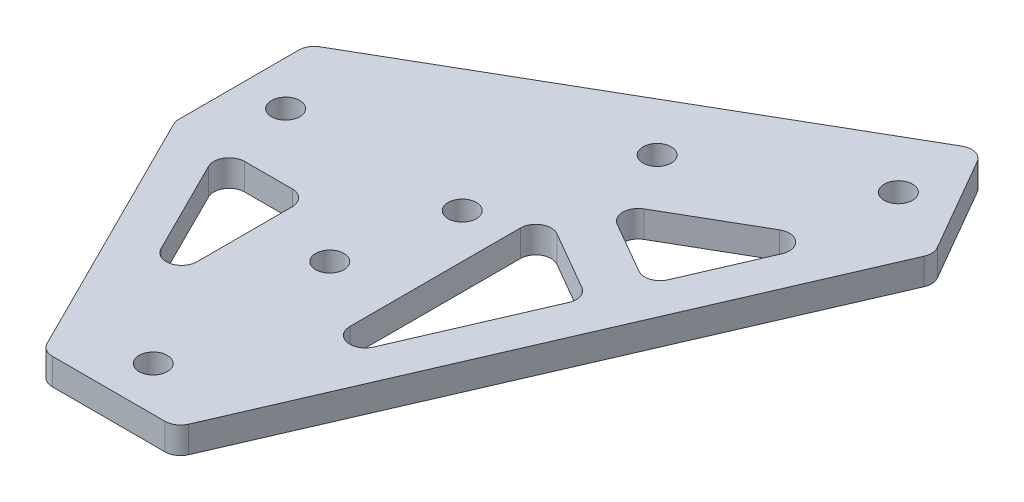
SolidWorks part; units mm, degrees
ref_plane "正面" through (0, 0, 0) normal (0, 0, 1) x (1, 0, 0)
ref_plane "平面" through (0, 0, 0) normal (0, 1, 0) x (1, 0, 0)
ref_plane "右側面" through (0, 0, 0) normal (1, 0, 0) x (0, 0, -1)
sketch "ｽｹｯﾁ2" plane through (0, 0.3953, 0) normal (0, 1, 0) x (1, 0, 0)
  line L0 (275.032, 154.7676) -> (267.532, 167.7579) construction
  line L1 (267.532, 167.7579) -> (163.6089, 107.7579) construction
  line L2 (163.6089, 107.7579) -> (171.1089, 94.7676) construction
  line L3 (171.1089, 94.7676) -> (275.032, 154.7676) construction
  line L4 (171.1089, 79.7676) -> (156.1089, 79.7676) construction
  line L5 (156.1089, 79.7676) -> (156.1089, -61.2324) construction
  line L6 (156.1089, -61.2324) -> (171.1089, -61.2324) construction
  line L7 (171.1089, -61.2324) -> (171.1089, 79.7676) construction
  line L8 (171.1089, 79.7676) -> (171.1089, 94.7676) construction
  line L9 (171.1089, 94.7676) -> (-48.8911, 94.7676) construction
  line L10 (-48.8911, 94.7676) -> (-48.8911, 79.7676) construction
  line L11 (-48.8911, 79.7676) -> (171.1089, 79.7676) construction
  line L12 (275.032, 154.7676) -> (267.532, 167.7579) construction
  line L13 (267.532, 167.7579) -> (163.6089, 107.7579) construction
  line L14 (163.6089, 107.7579) -> (171.1089, 94.7676) construction
  line L15 (171.1089, 94.7676) -> (275.032, 154.7676) construction
  line L16 (171.1089, 79.7676) -> (156.1089, 79.7676) construction
  line L17 (156.1089, 79.7676) -> (156.1089, -61.2324) construction
  line L18 (156.1089, -61.2324) -> (171.1089, -61.2324) construction
  line L19 (171.1089, -61.2324) -> (171.1089, 79.7676) construction
  line L20 (171.1089, 79.7676) -> (171.1089, 94.7676) construction
  line L21 (171.1089, 94.7676) -> (-48.8911, 94.7676) construction
  line L22 (-48.8911, 94.7676) -> (-48.8911, 79.7676) construction
  line L23 (-48.8911, 79.7676) -> (171.1089, 79.7676) construction
  line L24 (0, 15) -> (103.923, 75) construction
  line L25 (0, 0) -> (-220, 0) construction
  line L26 (0, 0) -> (0, 15) construction
  line L27 (0, 15) -> (-220, 15) construction
  line L28 (-220, 0) -> (-220, 15) construction
  line L29 (0, 0) -> (-15, 0) construction
  line L30 (0, 0) -> (0, -141) construction
  line L31 (0, -141) -> (-15, -141) construction
  line L32 (-15, 0) -> (-15, -141) construction
  line L33 (103.923, 75) -> (96.423, 87.9904) construction
  line L34 (96.423, 87.9904) -> (-7.5, 27.9904) construction
  line L35 (-7.5, 27.9904) -> (0, 15) construction
  dimension "D1" = 15
  dimension "D2" = 220
  dimension "D3" = 141
  dimension "D4" = 15
  dimension "D5" = 120
  dimension "D6" = 15
  dimension "D7" = 120
sketch "ｽｹｯﾁ4" plane through (0, 0, 0) normal (0, 1, 0) x (1, 0, 0)
  line L0 (103.923, 75) -> (96.423, 87.9904) construction
  line L1 (0, 15) -> (103.923, 75) construction
  line L2 (96.423, 87.9904) -> (-7.5, 27.9904) construction
  line L3 (-7.5, 27.9904) -> (0, 15) construction
  line L4 (0, -141) -> (-15, -141) construction
  line L5 (0, 0) -> (0, -141) construction
  line L6 (-15, 0) -> (-15, -141) construction
  line L7 (0, 0) -> (0, 15) construction
  line L8 (-220, 0) -> (-220, 15) construction
  line L9 (0, 0) -> (-220, 0) construction
  line L10 (0, 15) -> (-220, 15) construction
  line L11 (103.923, 75) -> (96.423, 87.9904) construction
  line L12 (0, 15) -> (103.923, 75) construction
  line L13 (96.423, 87.9904) -> (-7.5, 27.9904) construction
  line L14 (-7.5, 27.9904) -> (0, 15) construction
  line L15 (0, -141) -> (-15, -141) construction
  line L16 (0, 0) -> (0, -141) construction
  line L17 (-15, 0) -> (-15, -141) construction
  line L18 (0, 0) -> (0, 15) construction
  line L19 (-220, 0) -> (-220, 15) construction
  line L20 (0, 0) -> (-220, 0) construction
  line L21 (0, 15) -> (-220, 15) construction
  line L22 (-3.75, 21.4952) -> (17.9006, 33.9952) construction
  line L23 (0, 7.5) -> (-25, 7.5) construction
  line L24 (-7.5, 0) -> (-7.5, -25) construction
  line L25 (-30, 0) -> (-30, 15)
  line L26 (-30, 15) -> (18.4808, 42.9904)
  line L27 (18.4808, 42.9904) -> (25.9808, 30)
  line L28 (25.9808, 30) -> (0, -30)
  line L29 (0, -30) -> (-15, -30)
  line L30 (-15, -30) -> (-30, 0)
  circle A0 centre (0.5801, 23.9952) radius 1.6
  circle A1 centre (-5, 7.5) radius 1.6
  circle A2 centre (-7.5, -5) radius 1.6
  circle A3 centre (-7.5, -25) radius 1.6
  circle A4 centre (-25, 7.5) radius 1.6
  circle A5 centre (17.9006, 33.9952) radius 1.6
  dimension "D4" = 3.2
  dimension "D5" = 3.2
  dimension "D6" = 3.2
  dimension "D7" = 3.2
  dimension "D8" = 3.2
  dimension "D9" = 3.2
  dimension "D1" = 25
  dimension "D2" = 25
  dimension "D3" = 25
  dimension "D10" = 20
  dimension "D11" = 20
  dimension "D12" = 20
  dimension "D13" = 5
  dimension "D14" = 5
  dimension "D15" = 5
extrude "ﾎﾞｽ - 押し出し1" add sketch "ｽｹｯﾁ4" along normal mid plane 3
sketch "ｽｹｯﾁ5" plane through (0, 1.5, 0) normal (0, 1, 0) x (1, 0, 0)
  line L0 (-7.5, 27.9904) -> (0, 15) construction
  line L1 (0, 15) -> (103.923, 75) construction
  line L2 (0, 0) -> (0, 15) construction
  line L3 (0, 15) -> (-220, 15) construction
  line L4 (0, 0) -> (-220, 0) construction
  line L5 (-15, 0) -> (-15, -141) construction
  line L6 (-30, 0) -> (-15, -30)
  line L7 (-15, -30) -> (0, -30)
  line L8 (0, -30) -> (25.9808, 30)
  line L9 (25.9808, 30) -> (18.4808, 42.9904)
  line L10 (18.4808, 42.9904) -> (-30, 15)
  line L11 (-30, 15) -> (-30, 0)
  line L12 (-30, 0) -> (-15, -30)
  line L13 (-15, -30) -> (0, -30)
  line L14 (0, -30) -> (25.9808, 30)
  line L15 (25.9808, 30) -> (18.4808, 42.9904)
  line L16 (18.4808, 42.9904) -> (-30, 15)
  line L17 (-30, 15) -> (-30, 0)
  line L18 (0, 0) -> (0, -141) construction
  line L19 (-7.5, 27.9904) -> (0, 15)
  line L20 (0, 15) -> (103.923, 75)
  line L21 (0, 0) -> (0, 15)
  line L22 (0, 15) -> (-220, 15)
  line L23 (0, 0) -> (-220, 0)
  line L24 (-15, 0) -> (-15, -141)
  line L25 (0, 0) -> (0, -141)
  line L26 (-2.9552, -25.5) -> (20.9517, 29.7106)
  line L27 (20.9517, 29.7106) -> (16.8336, 36.8433)
  line L28 (16.8336, 36.8433) -> (-25.5, 12.4019)
  line L29 (-25.5, 12.4019) -> (-25.5, 1.0623)
  line L30 (-25.5, 1.0623) -> (-12.2188, -25.5)
  line L31 (-12.2188, -25.5) -> (-2.9552, -25.5)
  line L32 (0, 15) -> (11.6654, 8.265) construction
  line L33 (0, 15) -> (-10.5, 21.0622) construction
  line L34 (-13, 19.6188) -> (10.6654, 5.9555)
  line L37 (-21, 15) -> (-5.25, 24.0933) construction
  line L38 (12.6654, 10.5744) -> (-8, 22.5056)
  line L40 (0, 15) -> (3.4641, 13)
  line L41 (0, 15) -> (-3.4641, 17)
  line L42 (-4.6188, 15) -> (-2.3094, 19)
  line L43 (0, 7) -> (6.9282, 19)
  line L44 (1.25, 17.1651) -> (-9.25, 23.2272) construction
  line L47 (-1.25, 12.8349) -> (10.4154, 6.0999) construction
  circle A1 centre (0.5801, 23.9952) radius 1.6
  circle A2 centre (0.5801, 23.9952) radius 1.6
  circle A3 centre (-5, 7.5) radius 1.6
  circle A4 centre (-5, 7.5) radius 1.6
  circle A5 centre (-7.5, -5) radius 1.6
  circle A6 centre (-7.5, -5) radius 1.6
  circle A7 centre (-7.5, -25) radius 1.6
  circle A8 centre (-7.5, -25) radius 1.6
  circle A9 centre (-25, 7.5) radius 1.6
  circle A10 centre (-25, 7.5) radius 1.6
  circle A11 centre (17.9006, 33.9952) radius 1.6
  circle A12 centre (17.9006, 33.9952) radius 1.6
  point P58 (-3.4641, 17)
  point P61 (3.4641, 13)
  dimension "D9" = 2.5
  dimension "D12" = 60
  dimension "D13" = 4
  dimension "D14" = 4
  dimension "D1" = 0
  dimension "D2" = 0
  dimension "D3" = 0
  dimension "D4" = 0
  dimension "D5" = 0
  dimension "D6" = 0
  dimension "D7" = 0
  dimension "D8" = 4.5
extrude "ｶｯﾄ - 押し出し2" cut sketch "ｽｹｯﾁ5" against normal blind 3 contours L43 L38 L26 L20 | L38 L43 L20 | L21 L43 L34 | L43 L21 L25 L26 L34 | L23 L30 L24
fillet "ﾌｨﾚｯﾄ2" radius 1.75 15 edges at (-15, 0, 19.9377) (0, 0, 18.6752) (10.6654, 0, -5.9555) (12.6654, 0, -10.5744) (2.5, 0, -16.4434) (19.4424, 0, -26.2251) (-24.9688, 0, 0) (-15, 0, 30) (0, 0, 30) (25.9808, 0, -30) (18.4808, 0, -42.9904) (-30, 0, -15) (-30, 0, 0) (0, 0, -12.1132) (-15, 0, 0)
